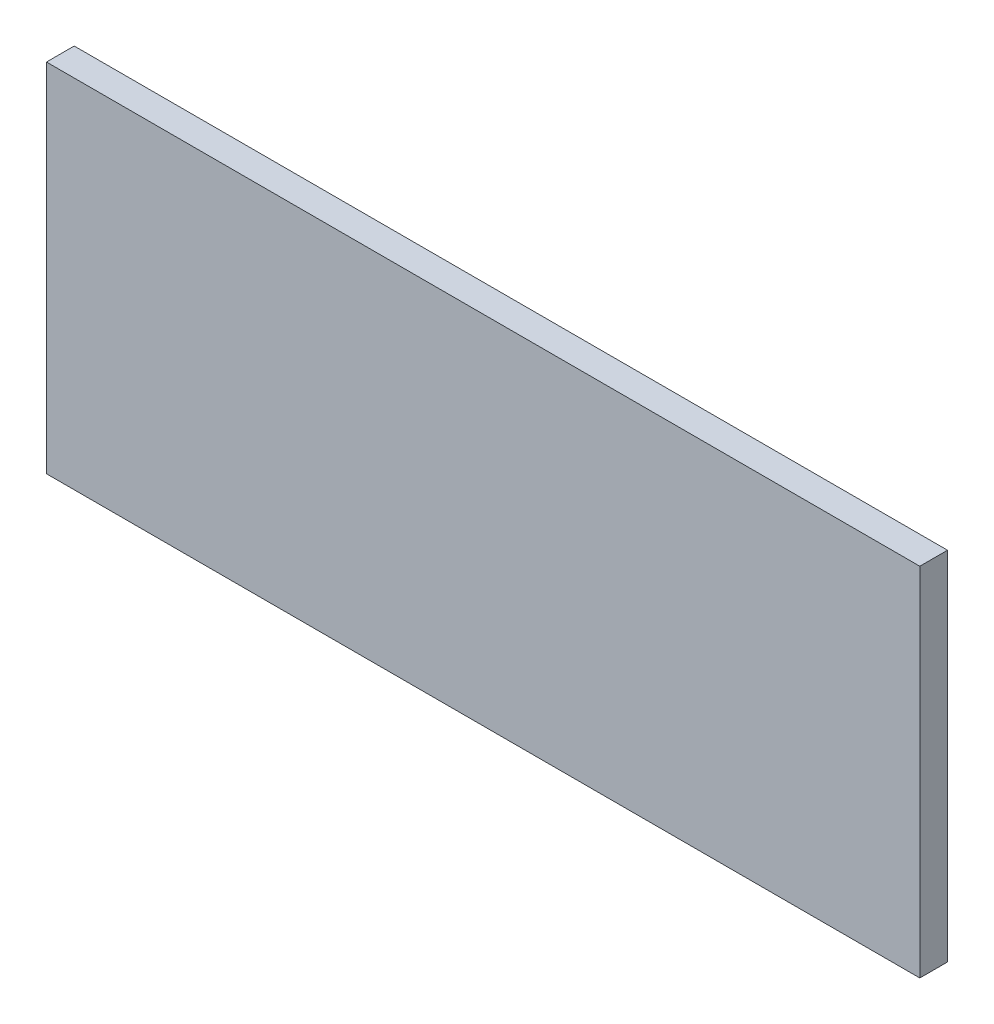
SolidWorks part; units mm, degrees
ref_plane "Front Plane" through (0, 0, 0) normal (0, 0, 1) x (1, 0, 0)
ref_plane "Top Plane" through (0, 0, 0) normal (0, 1, 0) x (1, 0, 0)
ref_plane "Right Plane" through (0, 0, 0) normal (1, 0, 0) x (0, 0, -1)
sketch "Sketch1" plane through (0, 0, 0) normal (0, 0, 1) x (1, 0, 0)
  line L1 (300, 5) -> (-300, 5)
  line L2 (300, 5) -> (300, 250)
  line L3 (300, 250) -> (-300, 250)
  line L4 (-300, 5) -> (-300, 250)
  dimension "D1" = 245
  dimension "D2" = 600
extrude "Boss-Extrude1" add sketch "Sketch1" along normal blind 19.05
